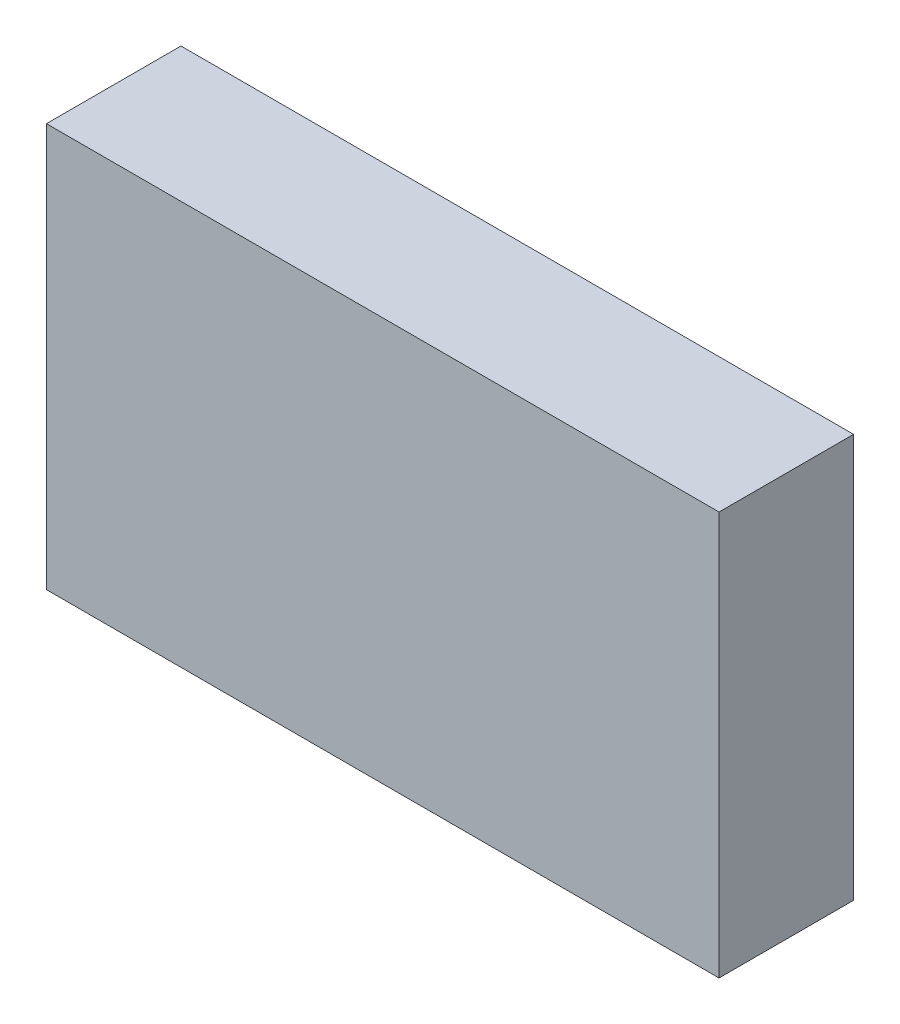
SolidWorks part; units mm, degrees
ref_plane "Front Plane" through (0, 0, 0) normal (0, 0, 1) x (1, 0, 0)
ref_plane "Top Plane" through (0, 0, 0) normal (0, 1, 0) x (1, 0, 0)
ref_plane "Right Plane" through (0, 0, 0) normal (1, 0, 0) x (0, 0, -1)
sketch "Sketch1" plane through (0, 0, 0) normal (0, 0, 1) x (1, 0, 0)
  line L1 (0, 0) -> (100, 0)
  line L2 (0, 0) -> (0, 60)
  line L3 (0, 60) -> (100, 60)
  line L4 (100, 0) -> (100, 60)
extrude "Boss-Extrude1" add sketch "Sketch1" along normal blind 20
